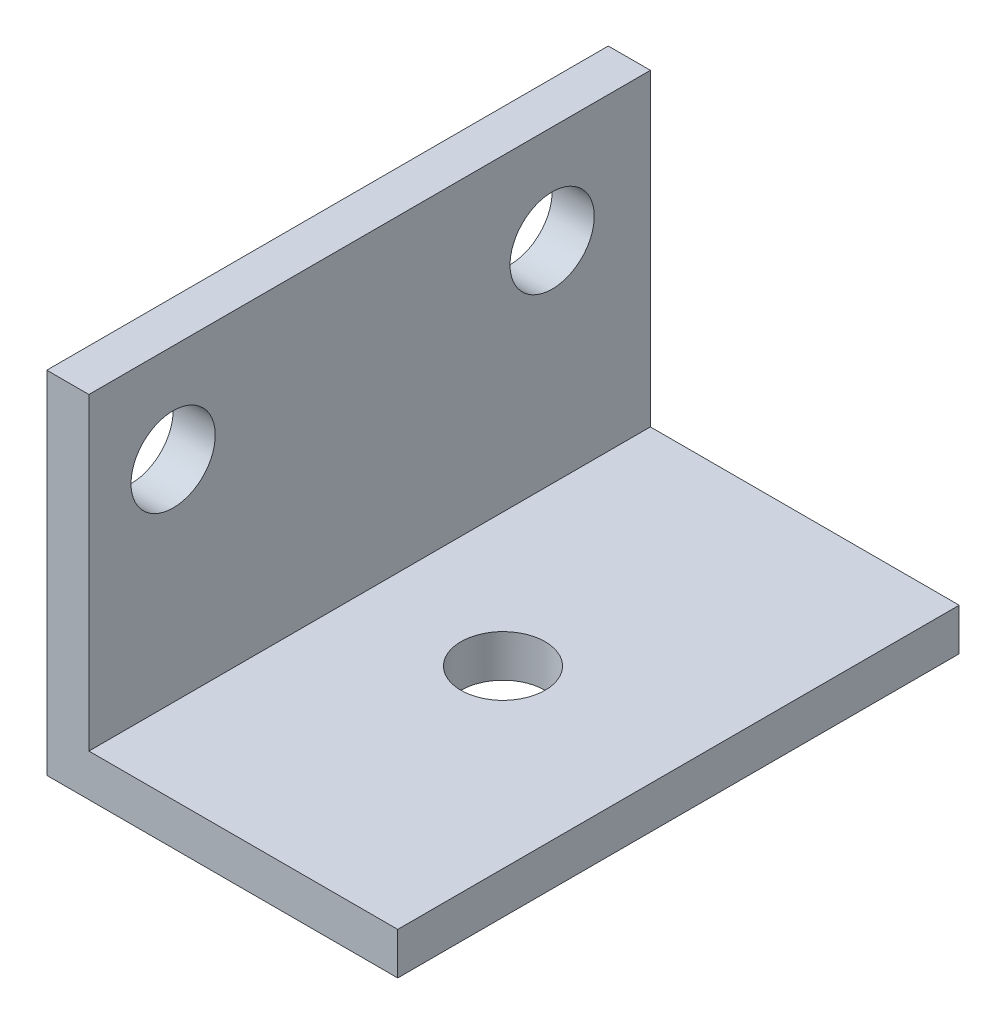
SolidWorks part; units mm, degrees
ref_plane "Alzado" through (0, 0, 0) normal (0, 0, 1) x (1, 0, 0)
ref_plane "Planta" through (0, 0, 0) normal (0, 1, 0) x (1, 0, 0)
ref_plane "Vista lateral" through (0, 0, 0) normal (1, 0, 0) x (0, 0, -1)
sketch "Croquis1" plane through (0, 0, 0) normal (0, 0, 1) x (1, 0, 0)
  line L0 (0, 0) -> (12.5, 0)
  line L1 (12.5, 0) -> (12.5, 1.5)
  line L2 (12.5, 1.5) -> (1.5, 1.5)
  line L3 (1.5, 1.5) -> (1.5, 12.5)
  line L4 (1.5, 12.5) -> (0, 12.5)
  line L5 (0, 12.5) -> (0, 0)
  dimension "D1" = 12.5
  dimension "D2" = 1.5
  dimension "D3" = 1.5
  dimension "D4" = 12.5
extrude "Saliente-Extruir1" add sketch "Croquis1" along normal blind 20
sketch "Croquis2" plane through (0, 0, 0) normal (-1, 0, 0) x (0, 0, 1)
  line L0 (0, 12.5) -> (0, 0) construction
  line L1 (20, 12.5) -> (20, 0) construction
  line L2 (20, 12.5) -> (0, 12.5) construction
  circle A0 centre (17, 9) radius 1.5
  circle A1 centre (3.5, 9) radius 1.5
  point P4 (14.977, 7.7345)
  dimension "D1" = 3
  dimension "D3" = 3
  dimension "D2" = 13.5
  dimension "D4" = 3.5
  dimension "D5" = 3
  dimension "D6" = 3.5
extrude "Cortar-Extruir1" cut sketch "Croquis2" against normal up to surface (1.5 mm away) up to face at (1.5, 7, 10)
sketch "Croquis3" plane through (0, 0, 0) normal (0, -1, 0) x (1, 0, 0)
  line L0 (-1.7912, 10) -> (15.1884, 10) construction
  line L2 (6.25, -4.4875) -> (6.25, 23.2913) construction
  line L6 (0, 0) -> (12.5, 0) construction
  line L8 (12.5, 20) -> (12.5, 0) construction
  circle A0 centre (6.25, 10) radius 1.5
  point P6 (0, 0)
  point P7 (0, 0)
  dimension "D1" = 3
  dimension "D2" = 10
  dimension "D3" = 6.25
extrude "Cortar-Extruir2" cut sketch "Croquis3" against normal up to surface (1.5 mm away) up to face at (7, 1.5, 10)
